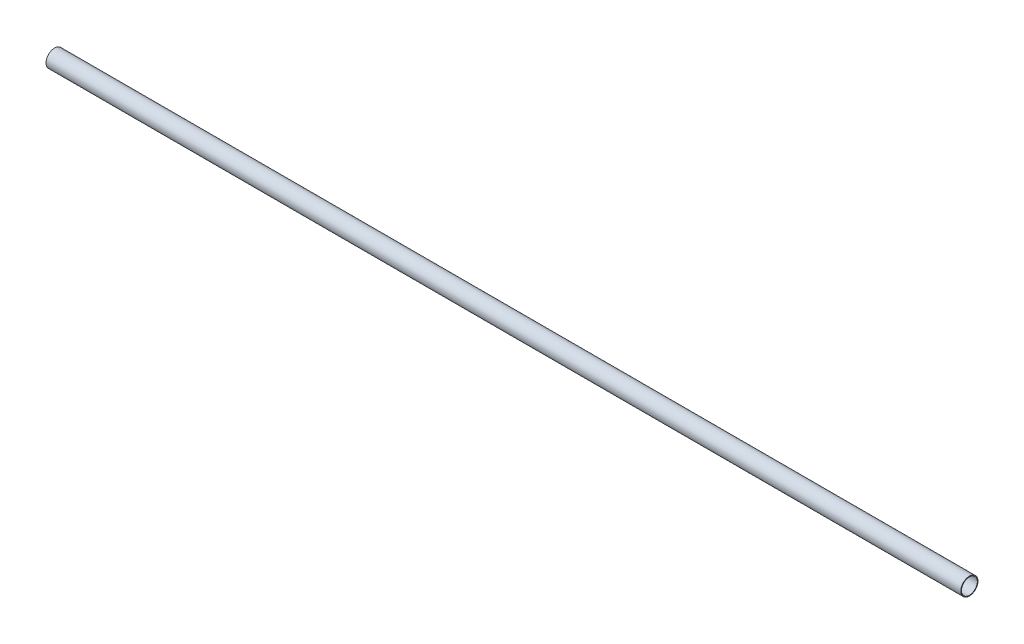
SolidWorks part; units mm, degrees
material "Acero al carbono no aleado"
ref_plane "Alzado" through (0, 0, 0) normal (0, 0, 1) x (1, 0, 0)
ref_plane "Planta" through (0, 0, 0) normal (0, 1, 0) x (1, 0, 0)
ref_plane "Vista lateral" through (0, 0, 0) normal (1, 0, 0) x (0, 0, -1)
sketch "Croquis1" plane through (0, 0, 0) normal (1, 0, 0) x (0, 0, -1)
  circle A0 centre (0, 0) radius 25.4
  circle A1 centre (0, 0) radius 23.4
  dimension "D1" = 50.8
  dimension "D2" = 2
extrude "Saliente-Extruir1" add sketch "Croquis1" along normal mid plane 2700
sketch "Croquis2" plane through (0, 0, 0) normal (0, 0, 1) x (1, 0, 0)
  line L1 (1260, -5) -> (-1260, -5)
  line L2 (1260, -5) -> (1260, 5)
  line L3 (1260, 5) -> (-1260, 5)
  line L4 (-1260, -5) -> (-1260, 5)
  line L5 (1260, -5) -> (-1260, 5) construction
  line L6 (1260, 5) -> (-1260, -5) construction
  circle A0 centre (-1339.4658, 0) radius 4
  point P0 (0, 0)
  dimension "D3" = 8
  dimension "D1" = 10
  dimension "D2" = 2520
extrude "Cortar-Extruir1" cut sketch "Croquis2" against normal through all
